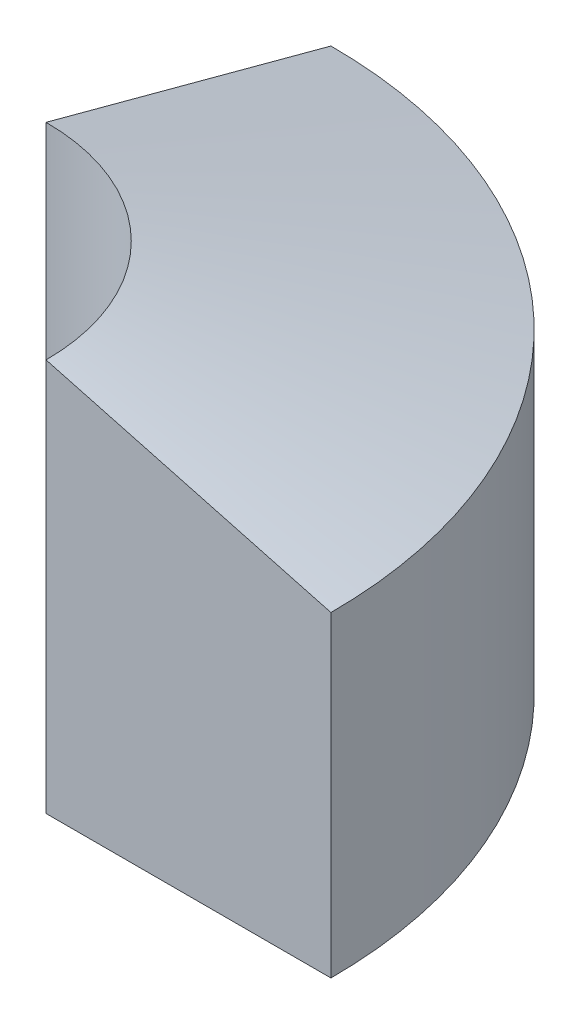
SolidWorks part; units mm, degrees
material "1.4301 (X5CrNi18-10)"
ref_plane "Vorne" through (0, 0, 0) normal (0, 0, 1) x (1, 0, 0)
ref_plane "Oben" through (0, 0, 0) normal (0, 1, 0) x (1, 0, 0)
ref_plane "Rechts" through (0, 0, 0) normal (1, 0, 0) x (0, 0, -1)
sketch "Skizze1" plane through (0, 0, 0) normal (0, 1, 0) x (1, 0, 0)
  line L0 (0, 33.9597) -> (0, 0) construction
  line L1 (0, 0) -> (39.0134, 0) construction
  line L2 (0, 31) -> (0, 13)
  line L3 (13, 0) -> (31, 0)
  arc A0 (0, 13) -> (13, 0) centre (0, 0) cw
  arc A1 (0, 31) -> (31, 0) centre (0, 0) cw
  dimension "D1" = 13
  dimension "D2" = 18
extrude "Aufsatz-Linear austragen1" add sketch "Skizze1" along normal mid plane 25
sketch "Skizze2" plane through (0, 0, 0) normal (0, 0, 1) x (1, 0, 0)
  line L0 (13, 12.5) -> (31, 12.5)
  line L1 (31, 12.5) -> (31, 7.5)
  line L2 (31, 12.5) -> (31, -12.5) construction
  line L3 (31, 7.5) -> (13, 12.3231)
  line L4 (13, 12.5) -> (13, -12.5) construction
  line L5 (13, 12.3231) -> (13, 12.5)
  line L6 (13, -12.5) -> (31, -12.5) construction
  dimension "D1" = 20
  dimension "D2" = 15
sweep "Schnitt-Austragung1" cut profiles "Skizze2" path edge at (21.9203, 12.5, -21.9203)
hole_wizard "M8 Gewindebohrung1" positions "Skizze4" profile "Skizze3" tap size "M8" standard "Gabler-Normteile"
sketch "Skizze4" plane through (0, -12.5, 0) normal (0, -1, 0) x (-1, 0, 0)
  line L0 (-13, 0) -> (-31, 0) construction
  line L1 (0, 31) -> (0, 13) construction
  line L2 (0, 0) -> (-6.7984, 20.9232) construction
  line L4 (0, 0) -> (-20.9232, 6.7984) construction
  arc A0 (-22, 0) -> (0, 22) centre (0, 0) cw construction
  arc A1 (0, 13) -> (-13, 0) centre (0, 0) ccw construction
  point P0 (-6.7984, 20.9232)
  point P2 (-20.9232, 6.7984)
  dimension "D1" = 18
  dimension "D2" = 18
sketch "Skizze3" plane through (6.7984, -12.5, -20.9232) normal (1, 0, 0) x (0, 0, -1)
  line L0 (0, 0) -> (0, 18.2929)
  line L1 (0, 18.2929) -> (3.4, 16.25)
  line L2 (3.4, 16.25) -> (3.4, 0)
  line L5 (3.4, 0) -> (0, 0)
  line L10 (0, 18.2929) -> (-3.4, 16.25) construction
  line L11 (0, -6.35) -> (0, 107.95) construction
  dimension "Bohrerdurchmesser" = 6.8
  dimension "Bohrungstiefe" = 16.25
  dimension "Spitzenwinkel" = 118
cosmetic thread "Bohrungsgewinde1" parameters "D1"=10, "D2"=8
cosmetic thread "Bohrungsgewinde2" parameters "D1"=10, "D2"=8
sketch "Skizze5" plane through (0, -12.5, 0) normal (0, -1, 0) x (1, 0, 0)
  line L0 (0, 0) -> (9.1924, -9.1924) construction
  arc A0 (0, -13) -> (13, 0) centre (0, 0) ccw construction
ref_plane "Ebene1" through (0, 0, 0) normal (0.7071, 0, 0.7071) x (0.7071, 0, -0.7071)
